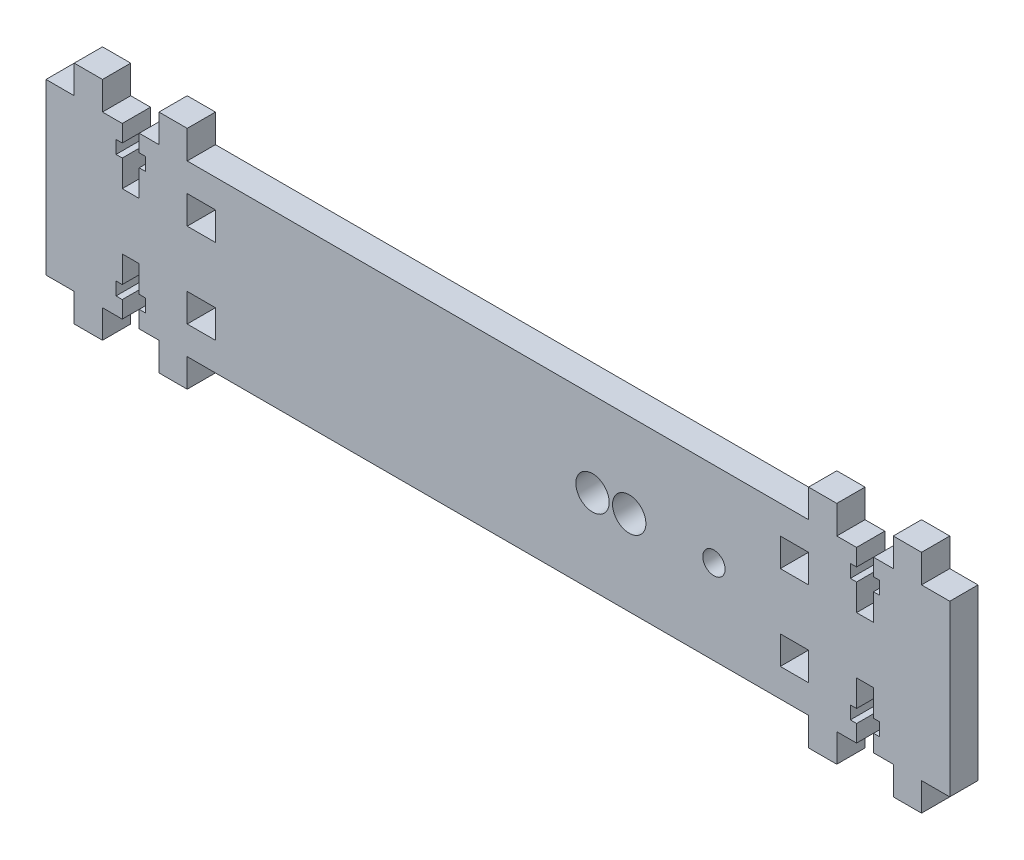
SolidWorks part; units mm, degrees
ref_plane "Front Plane" through (0, 0, 0) normal (0, 0, 1) x (1, 0, 0)
ref_plane "Top Plane" through (0, 0, 0) normal (0, 1, 0) x (1, 0, 0)
ref_plane "Right Plane" through (0, 0, 0) normal (1, 0, 0) x (0, 0, -1)
sketch "Sketch2" plane through (0, 0, 0) normal (0, 0, 1) x (1, 0, 0)
  line L0 (0, 0) -> (105.2075, 0) construction
  line L1 (0, 0) -> (0, 49.6369) construction
  line L2 (-80, 15) -> (80, 15) construction
  line L3 (80, 15) -> (80, -15) construction
  line L4 (80, -15) -> (-80, -15) construction
  line L5 (-80, -15) -> (-80, 15) construction
  line L6 (65, 15) -> (65, 3.7792) construction
  line L7 (66.5, 15) -> (70, 15)
  line L8 (70, 20) -> (75, 20)
  line L9 (75, 20) -> (75, 15)
  line L10 (70, 20) -> (70, 15)
  line L11 (63.5, 15) -> (60, 15)
  line L12 (60, 15) -> (60, 20)
  line L13 (60, 20) -> (55, 20)
  line L14 (55, 20) -> (55, 15)
  line L15 (66.5, 15) -> (63.5, 15) construction
  line L16 (63.5, 15) -> (63.5, 12)
  line L17 (63.5, 9.7) -> (62.4, 9.7)
  line L18 (67.6, 12) -> (67.6, 9.7)
  line L19 (62.4, 12) -> (63.5, 12)
  line L20 (63.5, 9.7) -> (63.5, 5)
  line L21 (63.5, 5) -> (66.5, 5)
  line L22 (66.5, 5) -> (66.5, 9.7)
  line L23 (66.5, 12) -> (67.6, 12)
  line L24 (62.4, 9.7) -> (62.4, 12)
  line L25 (67.6, 9.7) -> (66.5, 9.7)
  line L26 (66.5, 12) -> (66.5, 15)
  line L27 (65, 5) -> (65, 15) construction
  line L28 (-55, 20) -> (-55, 15)
  line L29 (-60, 20) -> (-55, 20)
  line L30 (-60, 15) -> (-60, 20)
  line L31 (-63.5, 15) -> (-60, 15)
  line L32 (-63.5, 15) -> (-63.5, 12)
  line L33 (-62.4, 12) -> (-63.5, 12)
  line L34 (-62.4, 9.7) -> (-62.4, 12)
  line L35 (-63.5, 9.7) -> (-62.4, 9.7)
  line L36 (-63.5, 9.7) -> (-63.5, 5)
  line L37 (-63.5, 5) -> (-66.5, 5)
  line L38 (-66.5, 5) -> (-66.5, 9.7)
  line L39 (-67.6, 9.7) -> (-66.5, 9.7)
  line L40 (-67.6, 12) -> (-67.6, 9.7)
  line L41 (-66.5, 12) -> (-67.6, 12)
  line L42 (-66.5, 12) -> (-66.5, 15)
  line L43 (-66.5, 15) -> (-70, 15)
  line L44 (-70, 20) -> (-70, 15)
  line L45 (-70, 20) -> (-75, 20)
  line L46 (-75, 20) -> (-75, 15)
  line L47 (55, -20) -> (55, -15)
  line L48 (60, -20) -> (55, -20)
  line L49 (60, -15) -> (60, -20)
  line L50 (63.5, -15) -> (60, -15)
  line L51 (63.5, -15) -> (63.5, -12)
  line L52 (62.4, -12) -> (63.5, -12)
  line L53 (62.4, -9.7) -> (62.4, -12)
  line L54 (63.5, -9.7) -> (62.4, -9.7)
  line L55 (63.5, -9.7) -> (63.5, -5)
  line L56 (63.5, -5) -> (66.5, -5)
  line L57 (66.5, -5) -> (66.5, -9.7)
  line L58 (67.6, -9.7) -> (66.5, -9.7)
  line L59 (67.6, -12) -> (67.6, -9.7)
  line L60 (66.5, -12) -> (67.6, -12)
  line L61 (66.5, -12) -> (66.5, -15)
  line L62 (66.5, -15) -> (70, -15)
  line L63 (70, -20) -> (70, -15)
  line L64 (70, -20) -> (75, -20)
  line L65 (75, -20) -> (75, -15)
  line L66 (-75, -20) -> (-75, -15)
  line L67 (-70, -20) -> (-75, -20)
  line L68 (-70, -20) -> (-70, -15)
  line L69 (-66.5, -15) -> (-70, -15)
  line L70 (-66.5, -12) -> (-66.5, -15)
  line L71 (-66.5, -12) -> (-67.6, -12)
  line L72 (-67.6, -12) -> (-67.6, -9.7)
  line L73 (-67.6, -9.7) -> (-66.5, -9.7)
  line L74 (-66.5, -5) -> (-66.5, -9.7)
  line L75 (-63.5, -5) -> (-66.5, -5)
  line L76 (-63.5, -9.7) -> (-63.5, -5)
  line L77 (-63.5, -9.7) -> (-62.4, -9.7)
  line L78 (-62.4, -9.7) -> (-62.4, -12)
  line L79 (-62.4, -12) -> (-63.5, -12)
  line L80 (-63.5, -15) -> (-63.5, -12)
  line L81 (-63.5, -15) -> (-60, -15)
  line L82 (-60, -15) -> (-60, -20)
  line L83 (-60, -20) -> (-55, -20)
  line L84 (-55, -20) -> (-55, -15)
  line L85 (-55, 15) -> (55, 15)
  line L86 (75, 15) -> (80, 15)
  line L87 (80, 15) -> (80, -15)
  line L88 (80, -15) -> (75, -15)
  line L89 (55, -15) -> (-55, -15)
  line L90 (-75, -15) -> (-80, -15)
  line L91 (-80, -15) -> (-80, 15)
  line L92 (-80, 15) -> (-75, 15)
  line L93 (-52.5, 5) -> (-52.5, -5) construction
  line L94 (-55, 5) -> (-55, 10)
  line L95 (-55, 5) -> (-50, 5)
  line L96 (-50, 5) -> (-50, 10)
  line L97 (-55, 10) -> (-50, 10)
  line L98 (-55, -5) -> (-55, -10)
  line L99 (-55, -5) -> (-50, -5)
  line L100 (-50, -5) -> (-50, -10)
  line L101 (-55, -10) -> (-50, -10)
  line L102 (-52.5, 0) -> (-59.4724, 0) construction
  line L103 (52.5, 5) -> (52.5, -5) construction
  line L104 (55, 5) -> (55, 10)
  line L105 (55, 5) -> (50, 5)
  line L106 (50, 5) -> (50, 10)
  line L107 (55, 10) -> (50, 10)
  line L108 (55, -5) -> (55, -10)
  line L109 (55, -5) -> (50, -5)
  line L110 (50, -5) -> (50, -10)
  line L111 (55, -10) -> (50, -10)
  line L112 (52.5, 0) -> (59.4724, 0) construction
  line L113 (20, 0) -> (20, 12) construction
  circle A0 centre (23.25, 0) radius 2.95
  circle A1 centre (16.75, 0) radius 2.95
  circle A2 centre (38.25, 0) radius 1.975
  circle A3 centre (-52.5, 0) radius 1.5 construction
  circle A4 centre (52.5, 0) radius 1.5 construction
  point P126 (0, 0)
  dimension "D13" = 5.9
  dimension "D17" = 3.95
  dimension "D19" = 3
  dimension "D23" = 3
  dimension "D1" = 55
  dimension "D2" = 10
  dimension "D3" = 5
  dimension "D4" = 5
  dimension "D5" = 5.2
  dimension "D6" = 3
  dimension "D7" = 2.3
  dimension "D8" = 3
  dimension "D9" = 10
  dimension "D10" = 30
  dimension "D11" = 5
  dimension "D12" = 50
  dimension "D14" = 6.5
  dimension "D15" = 20
  dimension "D16" = 15
  dimension "D18" = 5
  dimension "D20" = 5
  dimension "D21" = 10
  dimension "D22" = 5
  dimension "D24" = 5
  dimension "D25" = 10
extrude "Boss-Extrude1" add sketch "Sketch2" along normal blind 5
